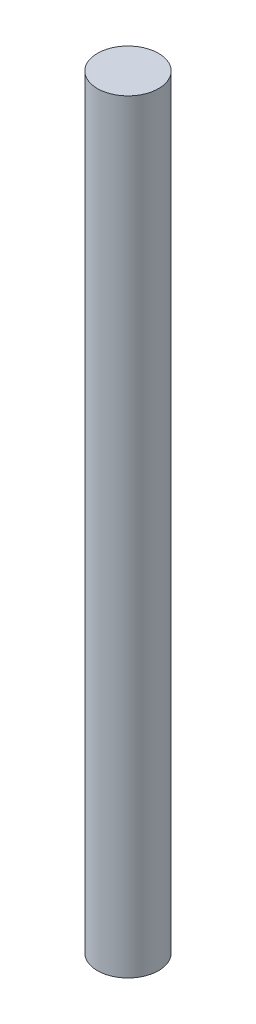
SolidWorks part; units mm, degrees
ref_plane "Front Plane" through (0, 0, 0) normal (0, 0, 1) x (1, 0, 0)
ref_plane "Top Plane" through (0, 0, 0) normal (0, 1, 0) x (1, 0, 0)
ref_plane "Right Plane" through (0, 0, 0) normal (1, 0, 0) x (0, 0, -1)
sketch "Sketch1" plane through (0, 0, 0) normal (0, 1, 0) x (1, 0, 0)
  circle A0 centre (0, 0) radius 30
extrude "Boss-Extrude1" add sketch "Sketch1" along normal blind 750
